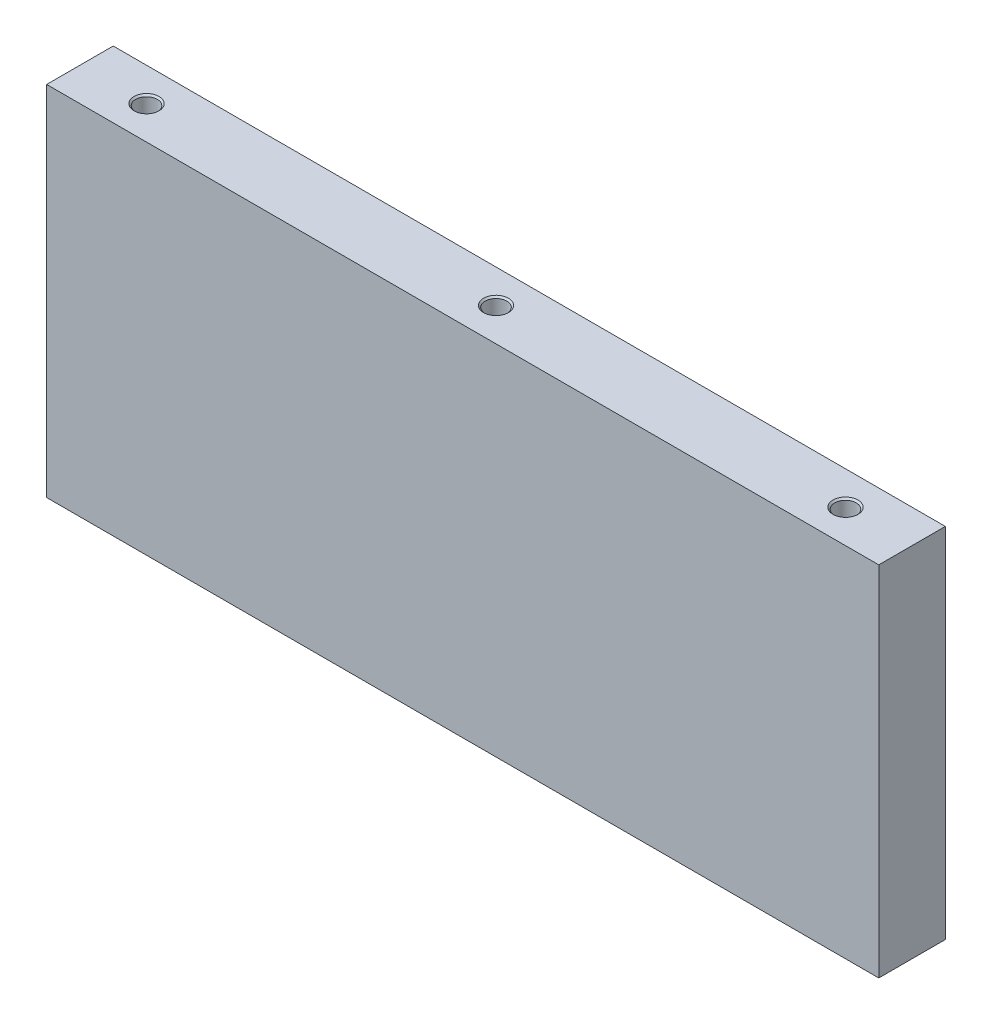
SolidWorks part; units mm, degrees
ref_plane "前基準面" through (0, 0, 0) normal (0, 0, 1) x (1, 0, 0)
ref_plane "上基準面" through (0, 0, 0) normal (0, 1, 0) x (1, 0, 0)
ref_plane "右基準面" through (0, 0, 0) normal (1, 0, 0) x (0, 0, -1)
sketch "草圖1" plane through (0, 0, 0) normal (0, 0, 1) x (1, 0, 0)
  line L1 (-50, 21.5) -> (50, 21.5)
  line L2 (-50, 21.5) -> (-50, -21.5)
  line L3 (-50, -21.5) -> (50, -21.5)
  line L4 (50, 21.5) -> (50, -21.5)
  line L5 (-50, 21.5) -> (50, -21.5) construction
  line L6 (-50, -21.5) -> (50, 21.5) construction
  point P0 (0, 0)
  dimension "D1" = 43
  dimension "D2" = 100
extrude "填料-伸長1" add sketch "草圖1" along normal blind 8
sketch "草圖2" plane through (0, 21.5, 0) normal (0, 1, 0) x (1, 0, 0)
  line L0 (-50, -8) -> (-50, 0) construction
  circle A0 centre (-42, -4) radius 1.3
  point P4 (-50, -4)
  dimension "D1" = 2.6
  dimension "D2" = 8
extrude "除料-伸長1" cut sketch "草圖2" against normal blind 8
pattern_linear "直線複製排列1" count 3 spacing 42 along (1, 0, 0) of "除料-伸長1"
mirror "鏡射1" about plane through (0, 0, 0) normal (0, 1, 0) of "除料-伸長1", "直線複製排列1"
chamfer "導角1" distance 0.2 6 edges at (42, -21.5, 5.3) (0, -21.5, 5.3) (-42, -21.5, 5.3) (-42, 21.5, 5.3) (0, 21.5, 5.3) (42, 21.5, 5.3)
